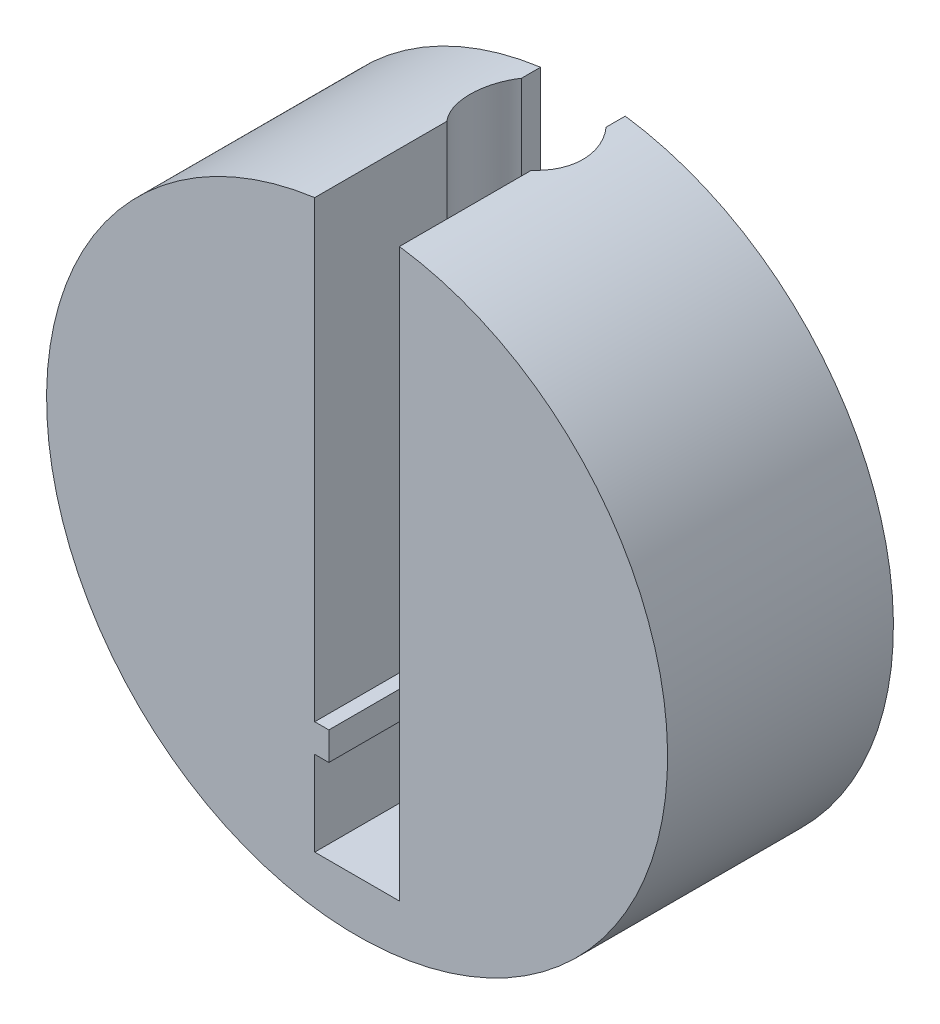
SolidWorks part; units mm, degrees
ref_plane "Front Plane" through (0, 0, 0) normal (0, 0, 1) x (1, 0, 0)
ref_plane "Top Plane" through (0, 0, 0) normal (0, 1, 0) x (1, 0, 0)
ref_plane "Right Plane" through (0, 0, 0) normal (1, 0, 0) x (0, 0, -1)
sketch "Sketch1" plane through (0, 0, 0) normal (0, 0, 1) x (1, 0, 0)
  line L0 (0, 0) -> (0, 11) construction
  line L1 (-1.5, 10.8972) -> (-1.5, -9.1833)
  line L2 (2, -5.1833) -> (-2, -5.1833)
  line L3 (2, -5.1833) -> (2, 10.8167)
  line L4 (2, 10.8167) -> (-2, 10.8167)
  line L5 (-2, -5.1833) -> (-2, 10.8167)
  line L6 (2, -5.1833) -> (-2, 10.8167) construction
  line L7 (2, 10.8167) -> (-2, -5.1833) construction
  line L8 (2, -5.1833) -> (-1, -5.1833)
  line L9 (2, -5.1833) -> (2, -6.1833)
  line L10 (2, -6.1833) -> (-1, -6.1833)
  line L11 (-1, -5.1833) -> (-1, -6.1833)
  line L12 (2, -6.1833) -> (-2, -6.1833)
  line L13 (2, -6.1833) -> (2, -9.1833)
  line L14 (2, -9.1833) -> (-2, -9.1833)
  line L15 (-2, -6.1833) -> (-2, -9.1833)
  line L16 (1.5, -9.1833) -> (1.5, 10.8972)
  circle A0 centre (0, 0) radius 11
  point P3 (0, 2.8167)
  dimension "D1" = 22
  dimension "D2" = 4
  dimension "D3" = 16
  dimension "D4" = 3
  dimension "D5" = 1
  dimension "D6" = 3
  dimension "D7" = 0.5
  dimension "D8" = 0.5
extrude "Boss-Extrude1" add sketch "Sketch1" along normal blind 8 contours L5 A0 L3 L9 L13 L14 L15 L12 L11 L2 | L12 L11 L2 L1 | L12 L15 L14 L1 | L5 L2 L1 L4 | L16 L2 L3 L4 | L16 L10 L9 L2 | L16 L14 L13 L10 | L4 A0 L16 | L1 A0 L4
sketch "Sketch8" plane through (0, 0, 0) normal (0, 1, 0) x (1, 0, 0)
  line L0 (-1.5, 0) -> (1.5, 0) construction
  line L1 (0, 0) -> (0, -2) construction
  circle A0 centre (0, -2) radius 2
  dimension "D1" = 4
sketch "Sketch4" plane through (0, 0, 0) normal (0, 0, -1) x (-1, 0, 0)
  line L0 (-2, 10.8167) -> (-2, -9.1833)
  line L1 (-2, -9.1833) -> (2, -9.1833)
  line L2 (2, -9.1833) -> (2, -6.1833)
  line L3 (2, -6.1833) -> (1, -6.1833)
  line L4 (1, -6.1833) -> (1, -5.1833)
  line L5 (1, -5.1833) -> (2, -5.1833)
  line L6 (2, -5.1833) -> (2, 10.8167)
  line L7 (-2, 10.8167) -> (2, 10.8167) construction
  line L8 (-1.5, 10.8972) -> (-1.5, -9.1833)
  line L9 (1.5, 10.8972) -> (1.5, -9.1833)
  circle A0 centre (0, 0) radius 11
  dimension "D1" = 22
  dimension "D2" = 0.5
  dimension "D3" = 0.5
  dimension "D4" = 20
  dimension "D5" = 4
  dimension "D6" = 0.5
extrude "pin hole" cut sketch "Sketch8" against normal up to surface (5.1833 mm away) and the other way through all up to face at (-1.25, -5.1833, 4)
sketch "Sketch6" plane through (0, 0, 0) normal (0, 0, -1) x (-1, 0, 0)
  line L0 (-11, 0) -> (11, 0) construction
  line L1 (-6, 1.5) -> (-4, -1.5) construction
  line L2 (-6, 1.5) -> (-4, 1.5)
  line L3 (-6, 1.5) -> (-6, -1.5)
  line L4 (-6, -1.5) -> (-4, -1.5)
  line L5 (-4, 1.5) -> (-4, -1.5)
  line L6 (4, 1.5) -> (6, 1.5)
  line L7 (4, 1.5) -> (4, -1.5)
  line L8 (4, -1.5) -> (6, -1.5)
  line L9 (6, 1.5) -> (6, -1.5)
  line L10 (4, 1.5) -> (6, -1.5) construction
  line L11 (-5, 0) -> (-11, 0) construction
  line L12 (5, 0) -> (11, 0) construction
  circle A1 centre (0, 0) radius 11 construction
  point P14 (-5, 0)
  point P15 (5, 0)
  dimension "D7" = 22
  dimension "D1" = 3
  dimension "D2" = 2
  dimension "D3" = 2
  dimension "D4" = 3
  dimension "D5" = 6
  dimension "D6" = 6
extrude "Cut-Extrude2" cut sketch "Sketch6" against normal blind 2 contours L5 L2 L3 L4 | L9 L6 L7 L8
sketch "Sketch7" plane through (0, 0, 8) normal (0, 0, 1) x (1, 0, 0)
  line L0 (-11, 0) -> (11, 0) construction
  line L1 (-5.99, 1.49) -> (-4.01, -1.49) construction
  line L2 (-5.99, 1.49) -> (-4.01, 1.49)
  line L3 (-5.99, 1.49) -> (-5.99, -1.49)
  line L4 (-5.99, -1.49) -> (-4.01, -1.49)
  line L5 (-4.01, 1.49) -> (-4.01, -1.49)
  line L6 (4.1, 1.4) -> (5.9, 1.4)
  line L7 (4.1, 1.4) -> (4.1, -1.4)
  line L8 (4.1, -1.4) -> (5.9, -1.4)
  line L9 (5.9, 1.4) -> (5.9, -1.4)
  line L10 (4.1, 1.4) -> (5.9, -1.4) construction
  line L11 (-5, 0) -> (-11, 0) construction
  line L12 (5, 0) -> (11, 0) construction
  arc A0 (-1.5, 10.8972) -> (1.5, 10.8972) centre (0, 0) ccw construction
  dimension "D1" = 1.98
  dimension "D2" = 2.98
  dimension "D3" = 1.8
  dimension "D4" = 2.8
  dimension "D5" = 6
  dimension "D6" = 6
equation "\"ET_circle_diam\"= 0.3mm'add to diameter of outer circle"
